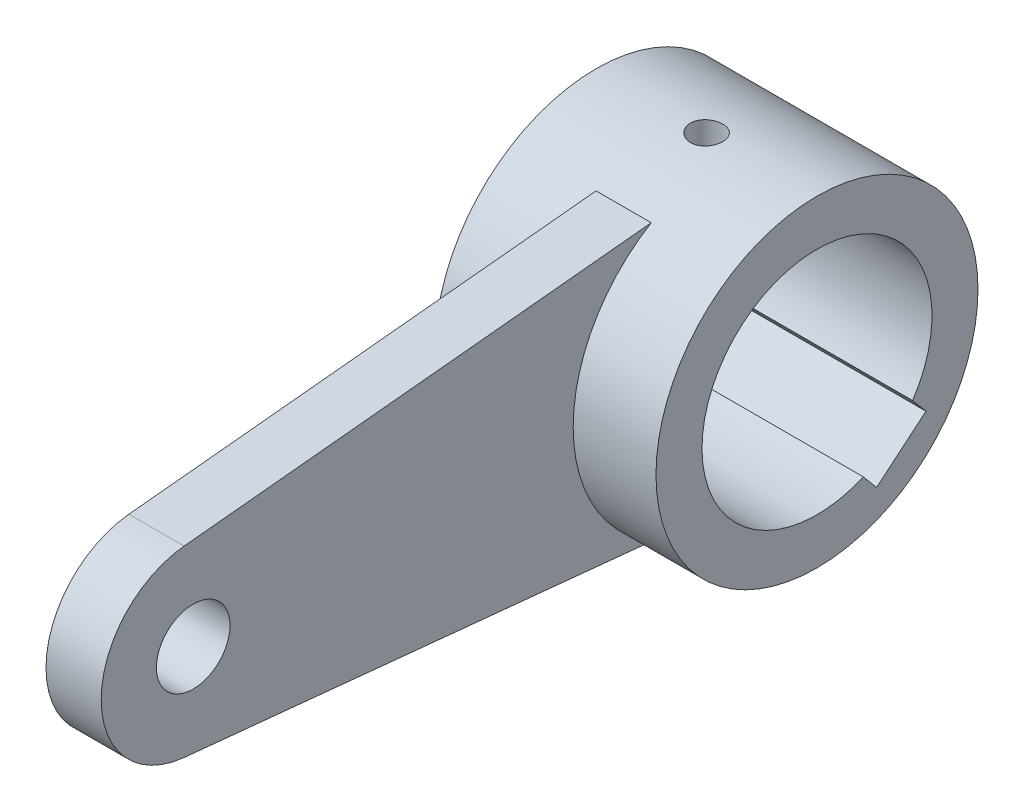
SolidWorks part; units mm, degrees
material "ASTM A36"
ref_plane "Front Plane" through (0, 0, 0) normal (0, 0, 1) x (1, 0, 0)
ref_plane "Top Plane" through (0, 0, 0) normal (0, 1, 0) x (1, 0, 0)
ref_plane "Right Plane" through (0, 0, 0) normal (1, 0, 0) x (0, 0, -1)
sketch "Sketch1" plane through (0, 0, 0) normal (1, 0, 0) x (0, 0, -1)
  circle A0 centre (0, 0) radius 25
  circle A1 centre (0, 0) radius 35
  dimension "D1" = 50
  dimension "D2" = 70
extrude "Boss-Extrude1" add sketch "Sketch1" along normal mid plane 48
sketch "Sketch2" plane through (0, 0, 0) normal (1, 0, 0) x (0, 0, -1)
  line L0 (-18.0278, 30) -> (-119.579, 19.9018)
  line L1 (-119.579, -19.9018) -> (-18.0278, -30)
  circle A0 centre (0, 0) radius 35 construction
  arc A1 (-119.579, 19.9018) -> (-119.579, -19.9018) centre (-117.6, 0) ccw
  circle A3 centre (0, 0) radius 35
  arc A4 (-18.0278, 30) -> (-18.0278, -30) centre (0, 0) ccw
  dimension "D2" = 20
  dimension "D1" = 117.6
  dimension "D3" = 60
  dimension "D4" = 0
extrude "Boss-Extrude2" add sketch "Sketch2" along normal mid plane 12
sketch "Sketch3" plane through (6, 0, 0) normal (1, 0, 0) x (0, 0, -1)
  circle A0 centre (-117.6, 0) radius 8
  dimension "D1" = 16
extrude "Cut-Extrude1" cut sketch "Sketch3" against normal blind 15
sketch "Sketch5" plane through (24, 0, 0) normal (1, 0, 0) x (0, 0, -1)
  line L0 (0, 0) -> (19.4876, -23.2245) construction
  line L1 (23.6818, -17.3328) -> (12.9571, -26.3318)
  line L2 (12.9571, -26.3318) -> (3.998, -15.6546)
  line L3 (3.998, -15.6546) -> (14.7226, -6.6556)
  line L4 (14.7226, -6.6556) -> (23.6818, -17.3328)
  line L5 (0, 0) -> (19.9004, 0) construction
  point P4 (18.3194, -21.8323)
  dimension "D1" = 310
  dimension "D2" = 14
  dimension "D3" = 28.5
extrude "Cut-Extrude2" cut sketch "Sketch5" against normal through all
ref_plane "Plane1" through (0, 35, 0) normal (0, 1, 0) x (-1, 0, 0)
sketch "Sketch6" plane through (0, 35, 0) normal (0, 1, 0) x (-1, 0, 0)
  circle A0 centre (0, 0) radius 3.5
  dimension "D1" = 7
extrude "Cut-Extrude3" cut sketch "Sketch6" against normal blind 24
